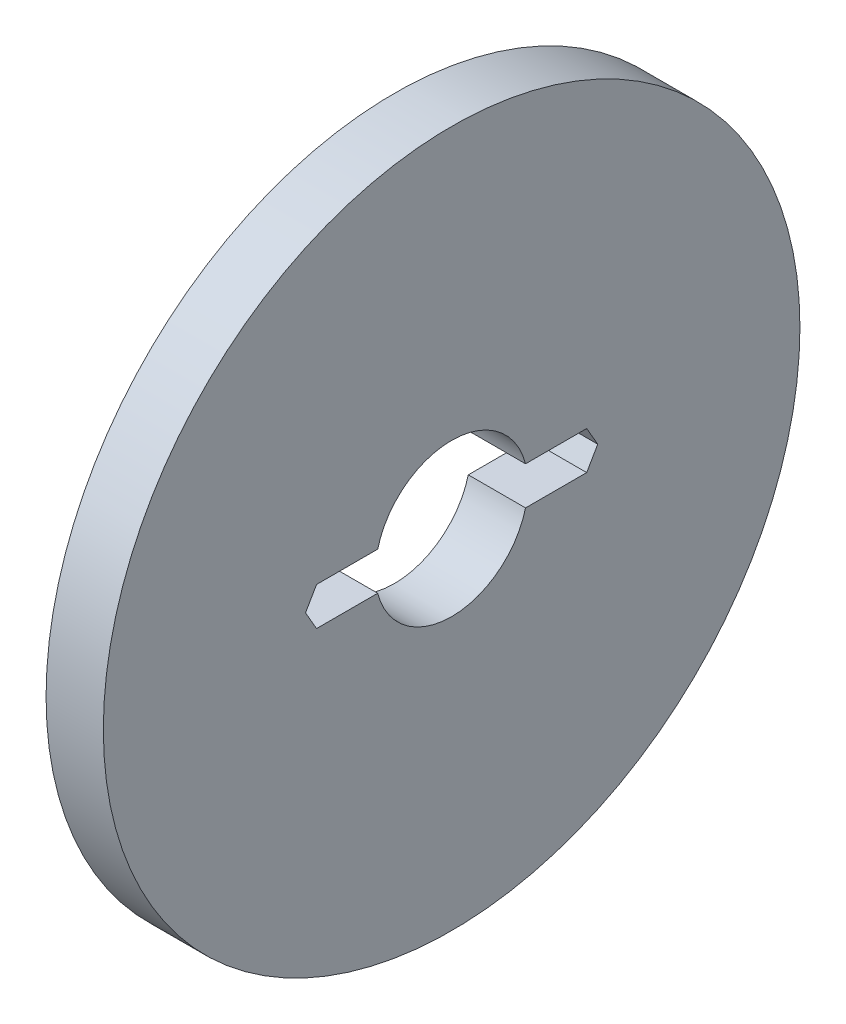
SolidWorks part; units mm, degrees
ref_plane "Front Plane" through (0, 0, 0) normal (0, 0, 1) x (1, 0, 0)
ref_plane "Top Plane" through (0, 0, 0) normal (0, 1, 0) x (1, 0, 0)
ref_plane "Right Plane" through (0, 0, 0) normal (1, 0, 0) x (0, 0, -1)
sketch "Sketch1" plane through (0, 0, 0) normal (1, 0, 0) x (0, 0, -1)
  line L0 (-18.25, 0) -> (18.25, 0) construction
  line L1 (5.9226, 1) -> (3.873, 1)
  line L2 (-3.873, 1) -> (-5.9226, 1)
  line L3 (5.9226, -1) -> (3.873, -1)
  line L4 (-3.873, -1) -> (-5.9226, -1)
  line L5 (5.9226, 1) -> (6.5, 1)
  line L6 (-7.6547, 0) -> (-7.0774, -1)
  line L7 (-7.0774, -1) -> (-5.9226, -1)
  line L8 (-5.9226, 1) -> (-7.0774, 1)
  line L9 (-7.0774, 1) -> (-7.6547, 0)
  line L10 (7.6547, 0) -> (7.0774, 1)
  line L11 (7.0774, 1) -> (6.5, 1)
  line L12 (6.5, -1) -> (7.0774, -1)
  line L13 (7.0774, -1) -> (7.6547, 0)
  line L14 (5.9226, -1) -> (6.5, -1)
  circle A0 centre (0, 0) radius 18.25
  arc A1 (-3.873, -1) -> (3.873, -1) centre (0, 0) ccw
  arc A2 (6.5, -1) -> (6.5, 1) centre (6.5, 0) ccw construction
  arc A3 (-6.5, 1) -> (-6.5, -1) centre (-6.5, 0) ccw construction
  arc A4 (3.873, 1) -> (-3.873, 1) centre (0, 0) ccw
  circle A5 centre (-6.5, 0) radius 1 construction
  circle A6 centre (6.5, 0) radius 1 construction
  point P9 (0, 0)
  dimension "D1" = 2
  dimension "D2" = 8
  dimension "D3" = 36.5
extrude "Boss-Extrude1" add sketch "Sketch1" along normal blind 3
